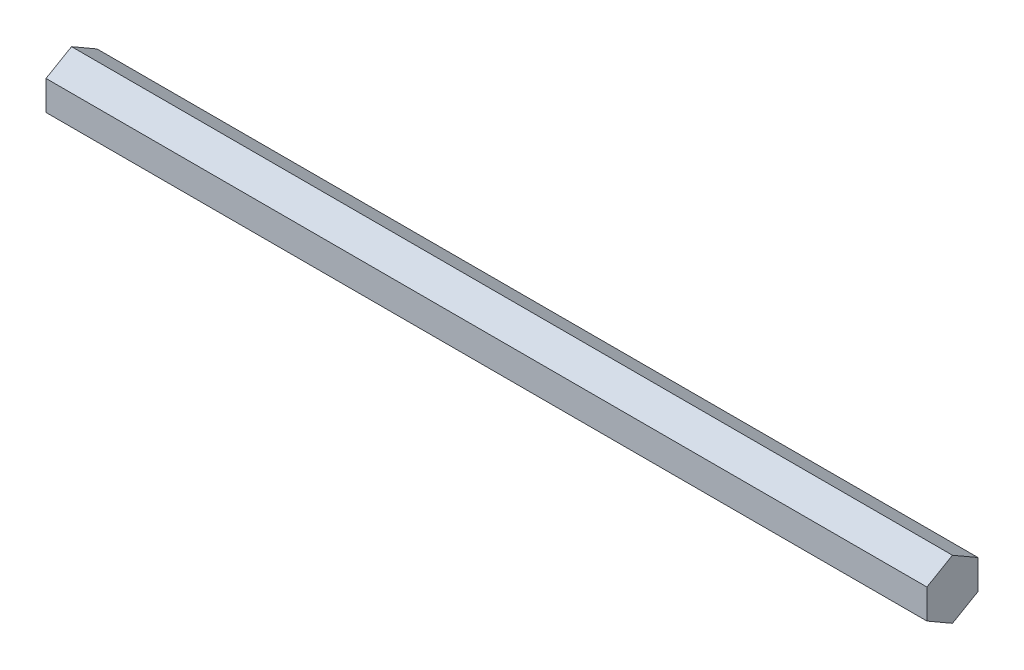
SolidWorks part; units mm, degrees
ref_plane "Front Plane" through (0, 0, 0) normal (0, 0, 1) x (1, 0, 0)
ref_plane "Top Plane" through (0, 0, 0) normal (0, 1, 0) x (1, 0, 0)
ref_plane "Right Plane" through (0, 0, 0) normal (1, 0, 0) x (0, 0, -1)
sketch "Hex Profile" plane through (0, 0, 0) normal (1, 0, 0) x (0, 0, -1)
  line L1 (4.1244, -2.3813) -> (4.1244, 2.3813)
  line L2 (4.1244, 2.3813) -> (0, 4.7625)
  line L3 (0, 4.7625) -> (-4.1244, 2.3813)
  line L4 (-4.1244, 2.3813) -> (-4.1244, -2.3813)
  line L5 (-4.1244, -2.3813) -> (0, -4.7625)
  line L6 (0, -4.7625) -> (4.1244, -2.3813)
  circle A0 centre (0, 0) radius 4.7625 construction
  dimension "D1" = 9.525
extrude "Axle" add sketch "Hex Profile" along normal blind 142.24
sketch "Motor Shaft Profile" plane through (0, 0, 0) normal (-1, 0, 0) x (0, 0, 1)
  line L0 (-1.6695, 2.4892) -> (1.6695, 2.4892)
  line L1 (0, -2.9972) -> (0, 2.4892) construction
  arc A0 (-1.6695, 2.4892) -> (1.6695, 2.4892) centre (0, 0) ccw
  arc A1 (1.6695, 2.4892) -> (-1.6695, 2.4892) centre (0, 0) ccw construction
  dimension "D1" = 5.9944
  dimension "D2" = 5.4864
extrude "Drive  Slot" cut sketch "Motor Shaft Profile" against normal blind 13.97
